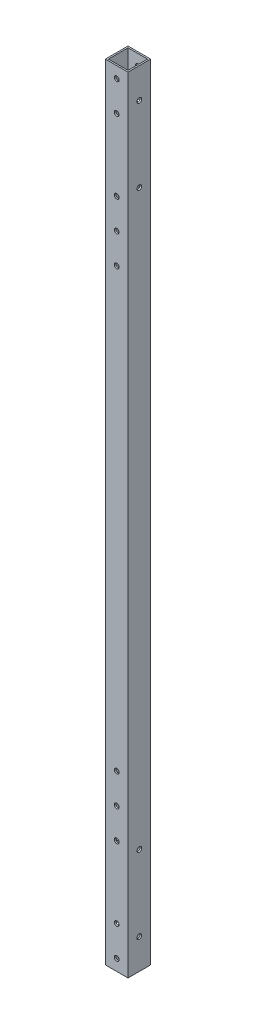
SolidWorks part; units mm, degrees
ref_plane "前视基准面" through (0, 0, 0) normal (0, 0, 1) x (1, 0, 0)
ref_plane "上视基准面" through (0, 0, 0) normal (0, 1, 0) x (1, 0, 0)
ref_plane "右视基准面" through (0, 0, 0) normal (1, 0, 0) x (0, 0, -1)
sketch "草图1" plane through (0, 0, 0) normal (0, 1, 0) x (1, 0, 0)
  line L1 (-7.5, -7.5) -> (7.5, -7.5)
  line L2 (-7.5, -7.5) -> (-7.5, 7.5)
  line L3 (-7.5, 7.5) -> (7.5, 7.5)
  line L4 (7.5, -7.5) -> (7.5, 7.5)
  line L5 (-7.5, -7.5) -> (7.5, 7.5) construction
  line L6 (-7.5, 7.5) -> (7.5, -7.5) construction
  point P0 (0, 0)
  dimension "D1" = 15
  dimension "D2" = 15
extrude "拉伸-薄壁1" add sketch "草图1" along normal blind 520 thin thin type one direction reverse wall 1
sketch "草图2" plane through (0, 0, 7.5) normal (0, 0, 1) x (1, 0, 0)
  line L0 (0, 0) -> (0, 520) construction
  line L1 (-7.5, 520) -> (7.5, 520) construction
  line L2 (-1000, 260) -> (49000, 260) construction
  line L3 (-7.5, 0) -> (7.5, 0) construction
  circle A0 centre (0, 7.5) radius 1.6
  circle A1 centre (0, 27.5) radius 1.6
  circle A2 centre (0, 67.5) radius 1.6 construction
  circle A3 centre (0, 75) radius 1.6
  circle A4 centre (0, 95) radius 1.6
  circle A5 centre (0, 115) radius 1.6
  circle A6 centre (0, 405) radius 1.6
  circle A7 centre (0, 425) radius 1.6
  circle A8 centre (0, 445) radius 1.6
  circle A9 centre (0, 452.5) radius 1.6 construction
  circle A10 centre (0, 492.5) radius 1.6
  circle A11 centre (0, 512.5) radius 1.6
  point P8 (0, 260)
  dimension "D1" = 3.2
  dimension "D2" = 7.5
  dimension "D3" = 20
  dimension "D4" = 40
  dimension "D5" = 20
  dimension "D6" = 20
  dimension "D7" = 165
extrude "切除-拉伸1" cut sketch "草图2" against normal through all
sketch "草图3" plane through (7.5, 0, 0) normal (1, 0, 0) x (0, 0, -1)
  line L0 (0, 0) -> (0, 520) construction
  line L1 (-7.5, 520) -> (7.5, 520) construction
  line L2 (-1000, 260) -> (49000, 260) construction
  circle A0 centre (0, 20) radius 1.6
  circle A1 centre (0, 70) radius 1.6
  circle A2 centre (0, 450) radius 1.6
  circle A3 centre (0, 500) radius 1.6
  point P12 (0, 260)
  dimension "D1" = 3.2
  dimension "D2" = 240
  dimension "D3" = 50
extrude "切除-拉伸2" cut sketch "草图3" against normal through all
